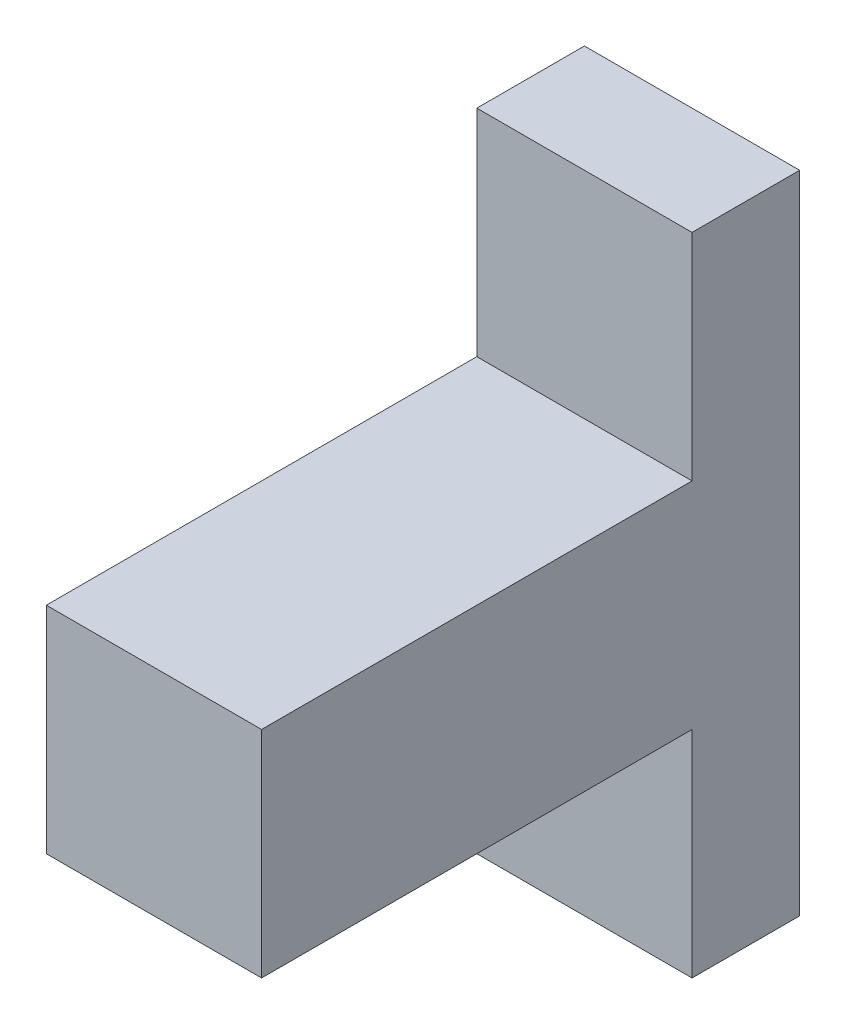
SolidWorks part; units mm, degrees
ref_plane "Front Plane" through (0, 0, 0) normal (0, 0, 1) x (1, 0, 0)
ref_plane "Top Plane" through (0, 0, 0) normal (0, 1, 0) x (1, 0, 0)
ref_plane "Right Plane" through (0, 0, 0) normal (1, 0, 0) x (0, 0, -1)
sketch "Sketch1" plane through (0, 0, 0) normal (0, 0, 1) x (1, 0, 0)
  line L1 (-10, 10) -> (10, 10)
  line L2 (-10, 10) -> (-10, -10)
  line L3 (-10, -10) -> (10, -10)
  line L4 (10, 10) -> (10, -10)
  line L5 (-10, 10) -> (10, -10) construction
  line L6 (-10, -10) -> (10, 10) construction
  point P0 (0, 0)
  dimension "D1" = 20
  dimension "D2" = 20
extrude "Boss-Extrude1" add sketch "Sketch1" along normal blind 50
sketch "Sketch3" plane through (0, 10, 0) normal (0, 1, 0) x (1, 0, 0)
  line L0 (10, -50) -> (10, 0) construction
  line L1 (-10, 0) -> (10, 0)
  line L2 (-10, 0) -> (-10, -10)
  line L3 (-10, -10) -> (10, -10)
  line L4 (10, 0) -> (10, -10)
  dimension "D1" = 10
extrude "Boss-Extrude3" add sketch "Sketch3" along normal blind 20
mirror "Mirror2" about plane through (0, 0, 0) normal (0, 1, 0) of "Boss-Extrude3"
